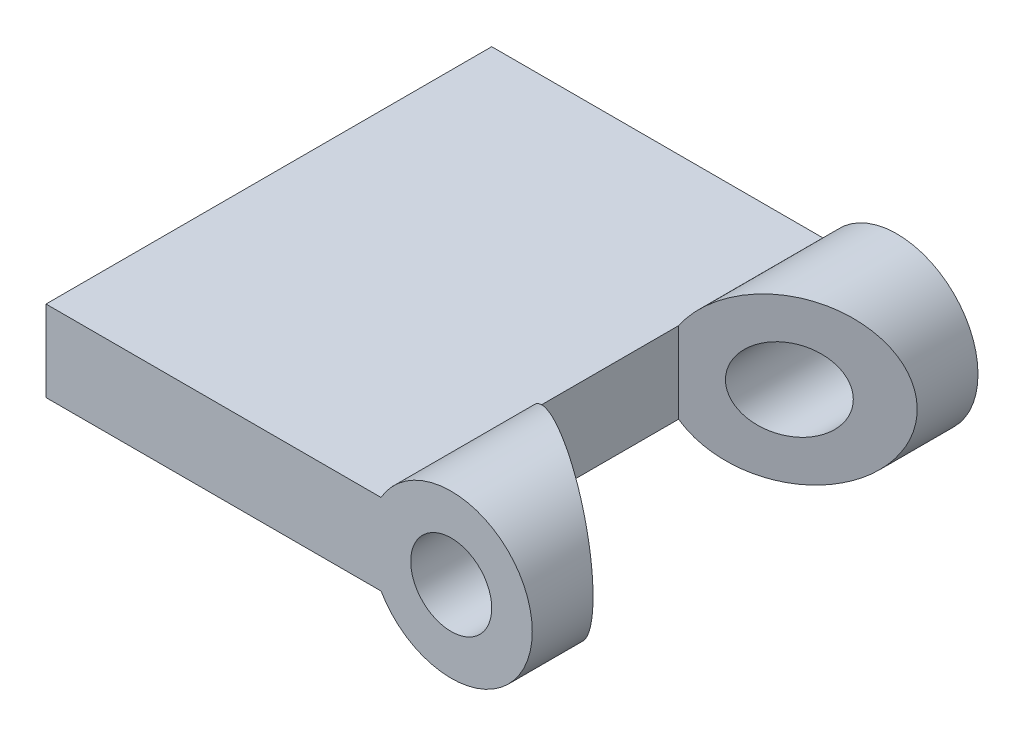
SolidWorks part; units mm, degrees
ref_plane "前视基准面" through (0, 0, 0) normal (0, 0, 1) x (1, 0, 0)
ref_plane "上视基准面" through (0, 0, 0) normal (0, 1, 0) x (1, 0, 0)
ref_plane "右视基准面" through (0, 0, 0) normal (1, 0, 0) x (0, 0, -1)
sketch "草图1" plane through (0, 0, 0) normal (0, 0, 1) x (1, 0, 0)
  circle A0 centre (0, 0) radius 20
  dimension "D1" = 40
extrude "凸台-拉伸1" add sketch "草图1" along normal mid plane 110
sketch "草图2" plane through (0, 0, 0) normal (0, 1, 0) x (1, 0, 0)
  line L0 (20, 55) -> (-20, 55) construction
  line L1 (0, 55) -> (-100, 55)
  line L2 (0, 55) -> (0, -55)
  line L3 (0, -55) -> (-100, -55)
  line L4 (-100, 55) -> (-100, -55)
  line L8 (-20, -55) -> (20, -55) construction
  point P9 (-62.3039, -55)
  dimension "D1" = 100
extrude "凸台-拉伸2" add sketch "草图2" along normal mid plane 20
sketch "草图3" plane through (0, 0, 55) normal (0, 0, 1) x (1, 0, 0)
  circle A0 centre (0, 0) radius 10
  dimension "D1" = 20
extrude "切除-拉伸1" cut sketch "草图3" against normal through all
sketch "草图5" plane through (0, 10, 0) normal (0, 1, 0) x (1, 0, 0)
  line L0 (20, -40) -> (-17.3205, -18.453)
  line L1 (20, -55) -> (20, 55) construction
  line L2 (-17.3205, -55) -> (-17.3205, 55) construction
  line L3 (20, -40) -> (20, 40)
  line L4 (-17.3205, -18.453) -> (-17.3205, 18.453)
  line L5 (-17.3205, 0) -> (20, 0) construction
  line L6 (20, 40) -> (-17.3205, 18.453)
  dimension "D1" = 40
  dimension "D2" = 120
extrude "切除-拉伸3" cut sketch "草图5" against normal through all both and the other way through all
sketch "草图4" plane through (0, 0, 0) normal (0, 0, 1) x (1, 0, 0)
  circle A1 centre (0, 0) radius 20
  circle A2 centre (0, 0) radius 20
  dimension "D1" = 0
